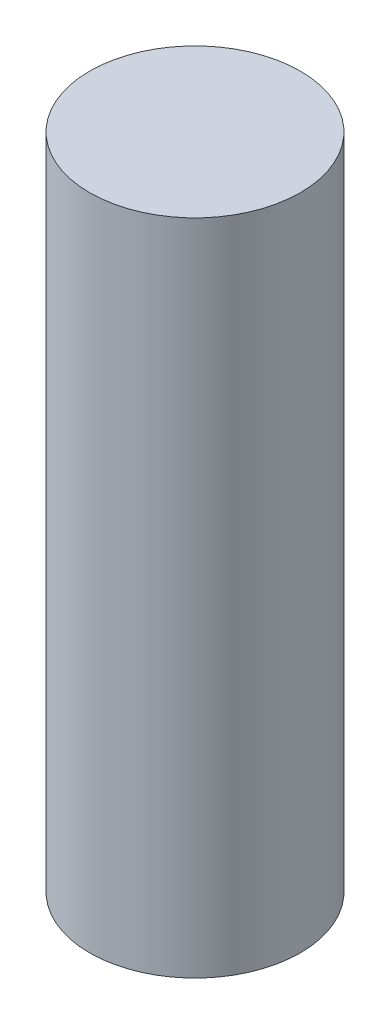
SolidWorks part; units mm, degrees
ref_plane "Front Plane" through (0, 0, 0) normal (0, 0, 1) x (1, 0, 0)
ref_plane "Top Plane" through (0, 0, 0) normal (0, 1, 0) x (1, 0, 0)
ref_plane "Right Plane" through (0, 0, 0) normal (1, 0, 0) x (0, 0, -1)
sketch "Sketch1" plane through (0, 0, 0) normal (0, 1, 0) x (1, 0, 0)
  circle A0 centre (0, 0) radius 2.4
  dimension "D1" = 4.8
extrude "Boss-Extrude1" add sketch "Sketch1" along normal blind 15
